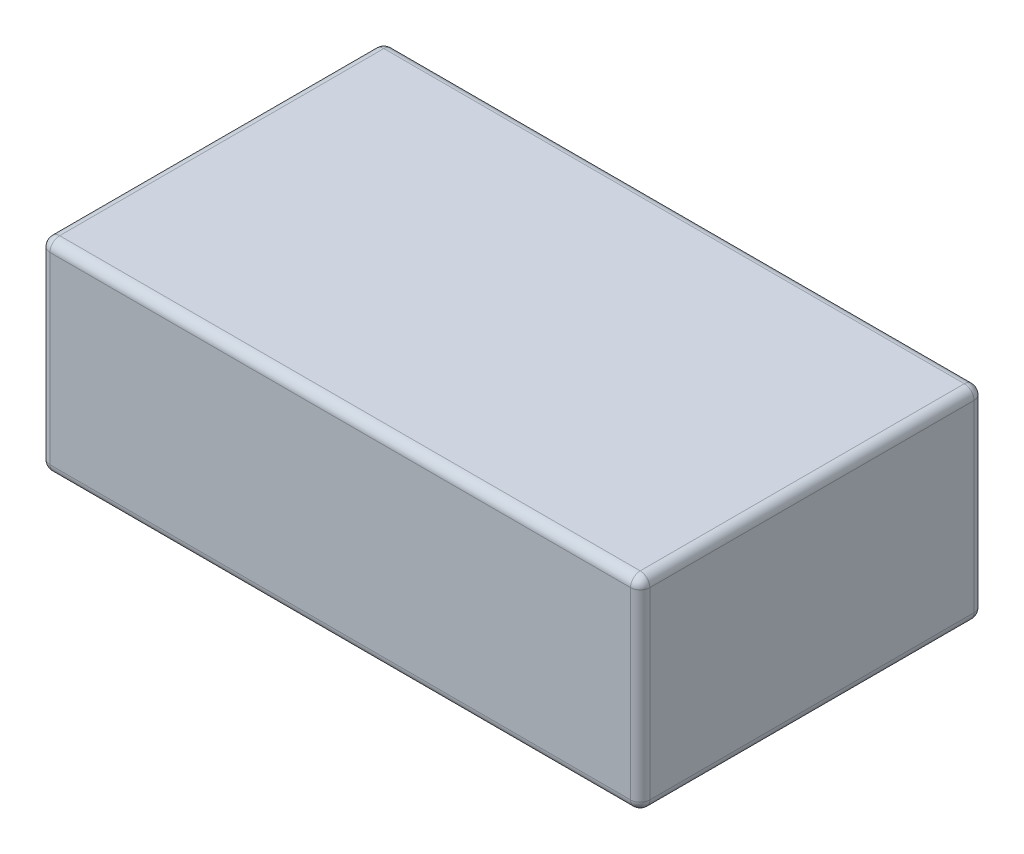
SolidWorks part; units mm, degrees
ref_plane "前视基准面" through (0, 0, 0) normal (0, 0, 1) x (1, 0, 0)
ref_plane "上视基准面" through (0, 0, 0) normal (0, 1, 0) x (1, 0, 0)
ref_plane "右视基准面" through (0, 0, 0) normal (1, 0, 0) x (0, 0, -1)
sketch "草图1" plane through (0, 0, 0) normal (0, 1, 0) x (1, 0, 0)
  line L1 (62, -35.5) -> (-62, -35.5)
  line L2 (62, -35.5) -> (62, 35.5)
  line L3 (62, 35.5) -> (-62, 35.5)
  line L4 (-62, -35.5) -> (-62, 35.5)
  line L5 (62, -35.5) -> (-62, 35.5) construction
  line L6 (62, 35.5) -> (-62, -35.5) construction
  point P0 (0, 0)
  dimension "D1" = 124
  dimension "D2" = 71
extrude "凸台-拉伸1" add sketch "草图1" along normal blind 42
fillet "圆角1" radius 2 12 edges at (-62, 0, 0) (-62, 21, -35.5) (0, 0, -35.5) (62, 21, -35.5) (0, 42, -35.5) (-62, 42, 0) (-62, 21, 35.5) (62, 0, 0) (0, 0, 35.5) (0, 42, 35.5) (62, 42, 0) (62, 21, 35.5)
